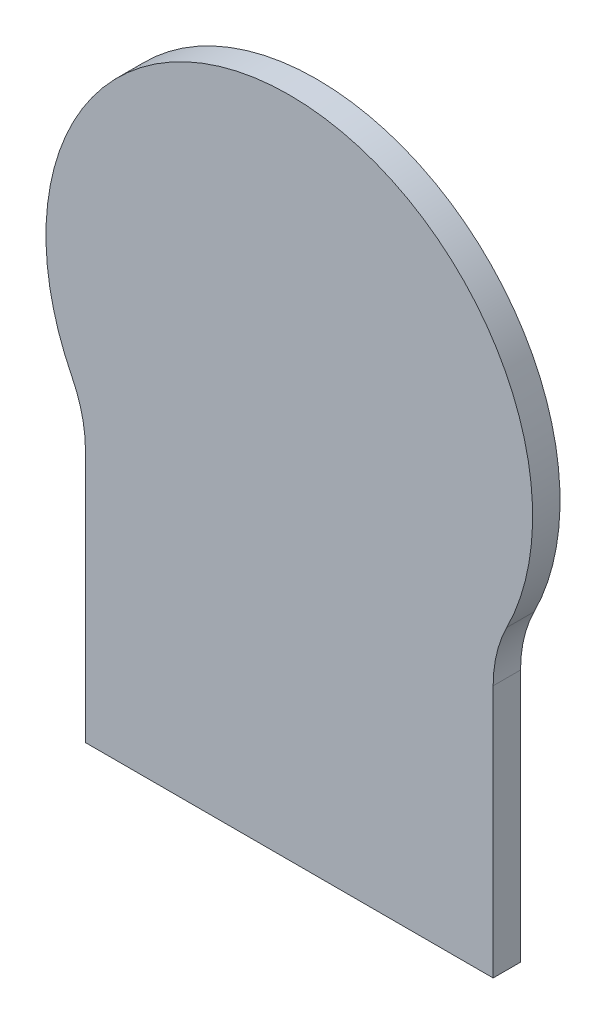
SolidWorks part; units mm, degrees
ref_plane "Front Plane" through (0, 0, 0) normal (0, 0, 1) x (1, 0, 0)
ref_plane "Top Plane" through (0, 0, 0) normal (0, 1, 0) x (1, 0, 0)
ref_plane "Right Plane" through (0, 0, 0) normal (1, 0, 0) x (0, 0, -1)
sketch "Sketch1" plane through (0, 0, 0) normal (0, 0, 1) x (1, 0, 0)
  line L0 (0, 0) -> (21.7747, 0) construction
  line L1 (0, 0) -> (0, 17.3344) construction
  line L2 (0, 0) -> (0, -13.4064) construction
  line L3 (-3.2, -6.5862) -> (3.2, -6.5862)
  line L4 (3.2, -6.5862) -> (3.2, -2.0862)
  line L5 (-3.2, -6.5862) -> (-3.2, -2.0862)
  circle A0 centre (0, 0) radius 3.82
  point P8 (0, 0)
  point P11 (0, -6.5862)
  dimension "D1" = 7.64
  dimension "D2" = 3.2
  dimension "D3" = 4.5
extrude "Boss-Extrude1" add sketch "Sketch1" along normal blind 0.43 contours A0 | A0 L5 L3 L4
fillet "Fillet1" radius 2 2 edges at (-3.2, -2.0862, 0.215) (3.2, -2.0862, 0.215)
